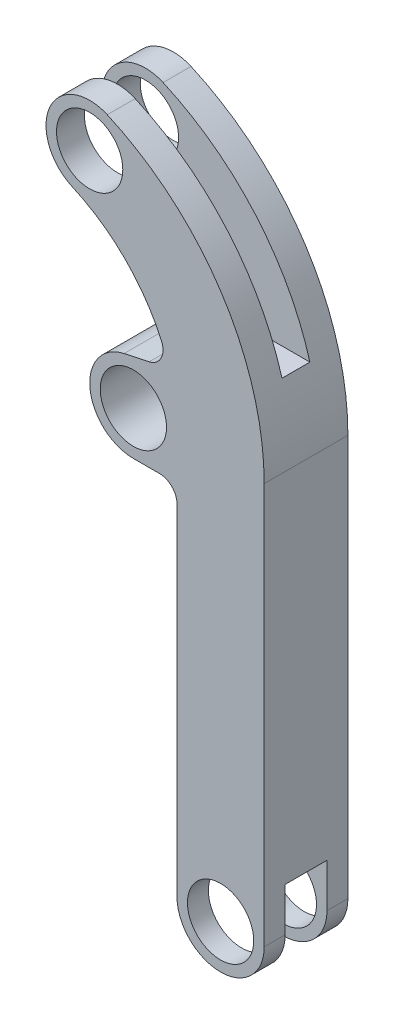
SolidWorks part; units mm, degrees
ref_plane "Alzado" through (0, 0, 0) normal (0, 0, 1) x (1, 0, 0)
ref_plane "Planta" through (0, 0, 0) normal (0, 1, 0) x (1, 0, 0)
ref_plane "Vista lateral" through (0, 0, 0) normal (1, 0, 0) x (0, 0, -1)
sketch "Croquis2" plane through (0, 0, 0) normal (0, 0, 1) x (1, 0, 0)
  line L0 (0, 115) -> (0, 0) construction
  line L1 (-12.5, 0) -> (-12.5, 97.5)
  line L2 (12.5, 0) -> (12.5, 115)
  line L3 (-142.407, 115) -> (142.407, 115) construction
  line L4 (-25, 102.5) -> (-17.5, 102.5)
  line L5 (0, 0) -> (-25, 115) construction
  line L6 (-25, 115) -> (-57.6336, 265.1147) construction
  line L7 (-37.5333, 212.7598) -> (-37.5333, 115) construction
  line L8 (-27.6554, 127.2147) -> (-20.4397, 128.7833)
  circle A0 centre (0, 0) radius 12.5
  circle A1 centre (0, 0) radius 9.5
  circle A2 centre (-25, 115) radius 12.5
  circle A3 centre (-25, 115) radius 9.5
  circle A4 centre (-37.5333, 172.6534) radius 12.5
  circle A5 centre (-37.5333, 172.6534) radius 9.5
  arc A6 (-16.9412, 135.7187) -> (-42.5916, 161.2226) centre (-63.0454, 115.0005) ccw
  arc A7 (-12.7466, 58.6344) -> (-12.5, 58.8554) centre (-63.0454, 115.0005) ccw
  arc A8 (12.5, 115) -> (-32.4751, 184.0842) centre (-63.0454, 115.0005) ccw
  arc A9 (-12.5, 97.5) -> (-17.5, 102.5) centre (-17.5, 97.5) ccw
  arc A10 (-16.9412, 135.7187) -> (-20.4397, 128.7833) centre (-21.5019, 133.6692) cw
  dimension "D1" = 25
  dimension "D2" = 19
  dimension "D4" = 19
  dimension "D3" = 25
  dimension "D8" = 19
  dimension "D9" = 25
  dimension "D11" = 5
  dimension "D5" = 115
  dimension "D6" = 25
  dimension "D7" = 0
  dimension "D10" = 59
  dimension "D12" = 0
  dimension "D13" = 0
  dimension "D14" = 0.001
extrude "Saliente-Extruir1" add sketch "Croquis2" along normal blind 24 contours A4 A5 | A6 A10 L8 A2 L4 A9 L1 A0 L2 A8 A4 | A2 A3 | A0 A1
sketch "Croquis5" plane through (-12.5, 0, 0) normal (-1, 0, 0) x (0, 0, 1)
  line L0 (24, 185.1534) -> (0, 185.1534) construction
  line L1 (8, 185.1534) -> (16, 185.1534)
  line L2 (8, 185.1534) -> (8, 135.7187)
  line L3 (8, 135.7187) -> (16, 135.7187)
  line L4 (16, 185.1534) -> (16, 135.7187)
  line L5 (24, 135.7187) -> (0, 135.7187) construction
  line L6 (24, 161.2226) -> (24, 185.1534) construction
  dimension "D1" = 8
  dimension "D2" = 8
extrude "Cortar-Extruir3" cut sketch "Croquis5" against normal through all both and the other way through all
sketch "Croquis6" plane through (-12.5, 0, 0) normal (-1, 0, 0) x (0, 0, 1)
  line L0 (0, -12.5) -> (24, -12.5) construction
  line L1 (18, -12.5) -> (6, -12.5)
  line L2 (18, -12.5) -> (18, 12.5)
  line L3 (18, 12.5) -> (6, 12.5)
  line L4 (6, -12.5) -> (6, 12.5)
  line L5 (0, 0) -> (0, -12.5) construction
  line L6 (24, -12.5) -> (24, 0) construction
  point P8 (0, -6.25)
  dimension "D1" = 25
  dimension "D2" = 6
  dimension "D3" = 6
extrude "Cortar-Extruir4" cut sketch "Croquis6" against normal through all both and the other way through all
sketch "Croquis7" plane through (0, 135.7187, 0) normal (0, 1, 0) x (1, 0, 0)
  line L0 (-32.4751, -16) -> (-50.0333, -16) construction
  line L1 (-50.0333, -8) -> (-35.5, -8)
  line L2 (-50.0333, -8) -> (-50.0333, -16)
  line L3 (-50.0333, -16) -> (-35.5, -16)
  line L4 (-35.5, -8) -> (-35.5, -16)
  line L5 (-37.5, 0) -> (-37.5, -24) construction
  dimension "D1" = 2
extrude "Cortar-Extruir5" cut sketch "Croquis7" against normal through all both and the other way through all
